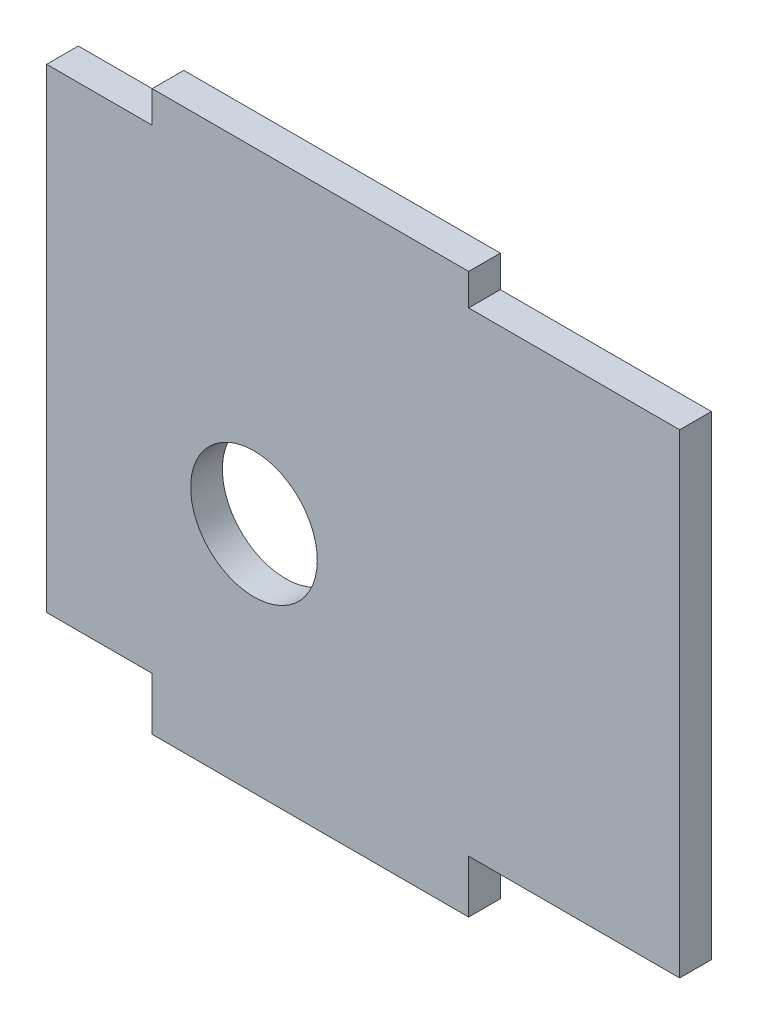
SolidWorks part; units mm, degrees
material "PVC rigido"
ref_plane "Piano frontale" through (0, 0, 0) normal (0, 0, 1) x (1, 0, 0)
ref_plane "Piano superiore" through (0, 0, 0) normal (0, 1, 0) x (1, 0, 0)
ref_plane "Piano destro" through (0, 0, 0) normal (1, 0, 0) x (0, 0, -1)
sketch "Schizzo1" plane through (0, 0, 0) normal (0, 0, 1) x (1, 0, 0)
  line L0 (47.5, -50) -> (17.5, -50) construction
  line L1 (17.5, 3) -> (47.5, 3)
  line L2 (17.5, 3) -> (17.5, -50)
  line L3 (17.5, -50) -> (47.5, -50)
  line L4 (47.5, 3) -> (47.5, -50)
  line L5 (47.5, 3) -> (17.5, 3) construction
extrude "Estrusione-Estrusione1" add sketch "Schizzo1" along normal blind 3
sketch "Schizzo3" plane through (0, 0, 3) normal (0, 0, 1) x (1, 0, 0)
  line L0 (17.5, 3) -> (17.5, -50) construction
  line L1 (17.5, 0) -> (7.5, 0)
  line L2 (17.5, 0) -> (17.5, -45)
  line L3 (17.5, -45) -> (7.5, -45)
  line L4 (7.5, 0) -> (7.5, -45)
  line L5 (47.5, -50) -> (47.5, 3) construction
  line L6 (47.5, 0) -> (67.5, 0)
  line L7 (47.5, 0) -> (47.5, -45)
  line L8 (47.5, -45) -> (67.5, -45)
  line L9 (67.5, 0) -> (67.5, -45)
  line L10 (8, -45) -> (17.5, -45) construction
  line L11 (47.5, 0) -> (57, 0) construction
  dimension "D1" = 10
  dimension "D2" = 20
extrude "Estrusione-Estrusione2" add sketch "Schizzo3" against normal up to surface (3 mm away) up to face at (32.5, -23.5, 0)
ref_plane "Piano1" through (65, -50, -140) normal (0, 1, 0) x (1, 0, 0)
sketch "Schizzo5" plane through (0, 0, 3) normal (0, 0, 1) x (1, 0, 0)
  circle A0 centre (27.15, -27.9) radius 6
  circle A1 centre (27.05, -28.3376) radius 6 construction
extrude "Taglio-Estrusione1" cut sketch "Schizzo5" against normal through all
